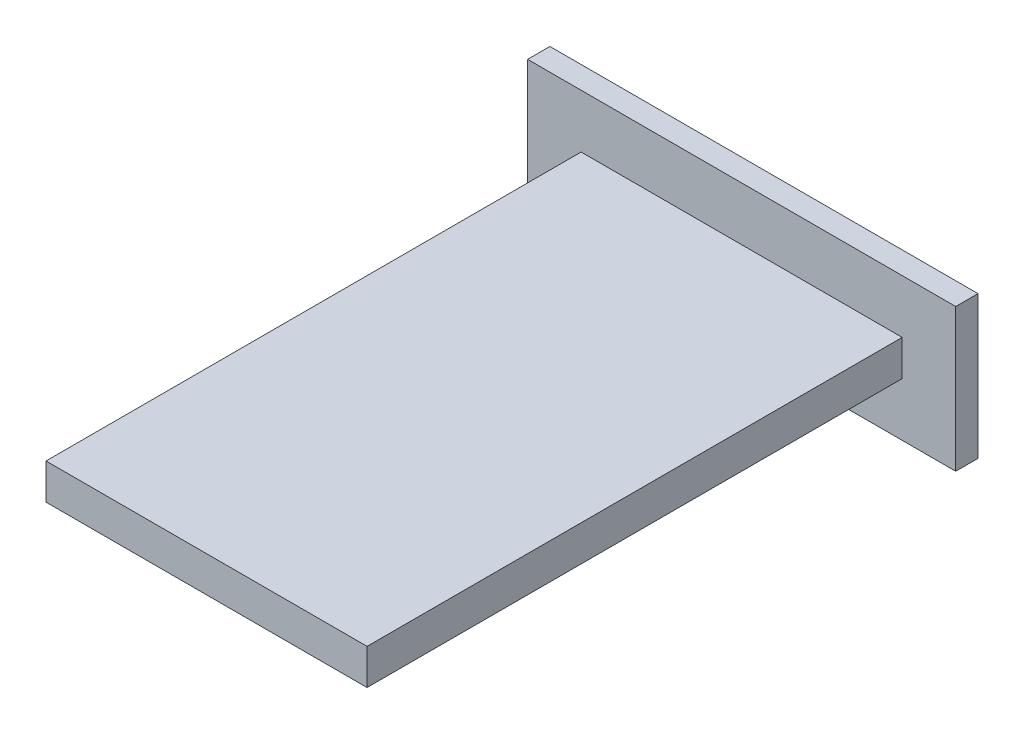
SolidWorks part; units mm, degrees
ref_plane "Front Plane" through (0, 0, 0) normal (0, 0, 1) x (1, 0, 0)
ref_plane "Top Plane" through (0, 0, 0) normal (0, 1, 0) x (1, 0, 0)
ref_plane "Right Plane" through (0, 0, 0) normal (1, 0, 0) x (0, 0, -1)
sketch "Sketch1" plane through (0, 0, 0) normal (0, 1, 0) x (1, 0, 0)
  line L1 (-9, -15) -> (9, -15)
  line L2 (-9, -15) -> (-9, 15)
  line L3 (-9, 15) -> (9, 15)
  line L4 (9, -15) -> (9, 15)
  line L5 (-9, -15) -> (9, 15) construction
  line L6 (-9, 15) -> (9, -15) construction
  point P0 (0, 0)
  dimension "D1" = 18
  dimension "D2" = 30
extrude "Boss-Extrude1" add sketch "Sketch1" along normal blind 2
sketch "Sketch2" plane through (0, 0, -15) normal (0, 0, -1) x (-1, 0, 0)
  line L5 (-9, 1) -> (9, 1) construction
  line L6 (-9, 2) -> (-9, 0) construction
  line L7 (9, 2) -> (9, 0) construction
  line L9 (-12, -3) -> (12, -3)
  line L10 (-12, -3) -> (-12, 5)
  line L11 (-12, 5) -> (12, 5)
  line L12 (12, -3) -> (12, 5)
  line L13 (-12, -3) -> (12, 5) construction
  line L14 (-12, 5) -> (12, -3) construction
  point P7 (0, 1)
  dimension "D1" = 3
  dimension "D2" = 3
extrude "Boss-Extrude2" add sketch "Sketch2" along normal blind 1.25
